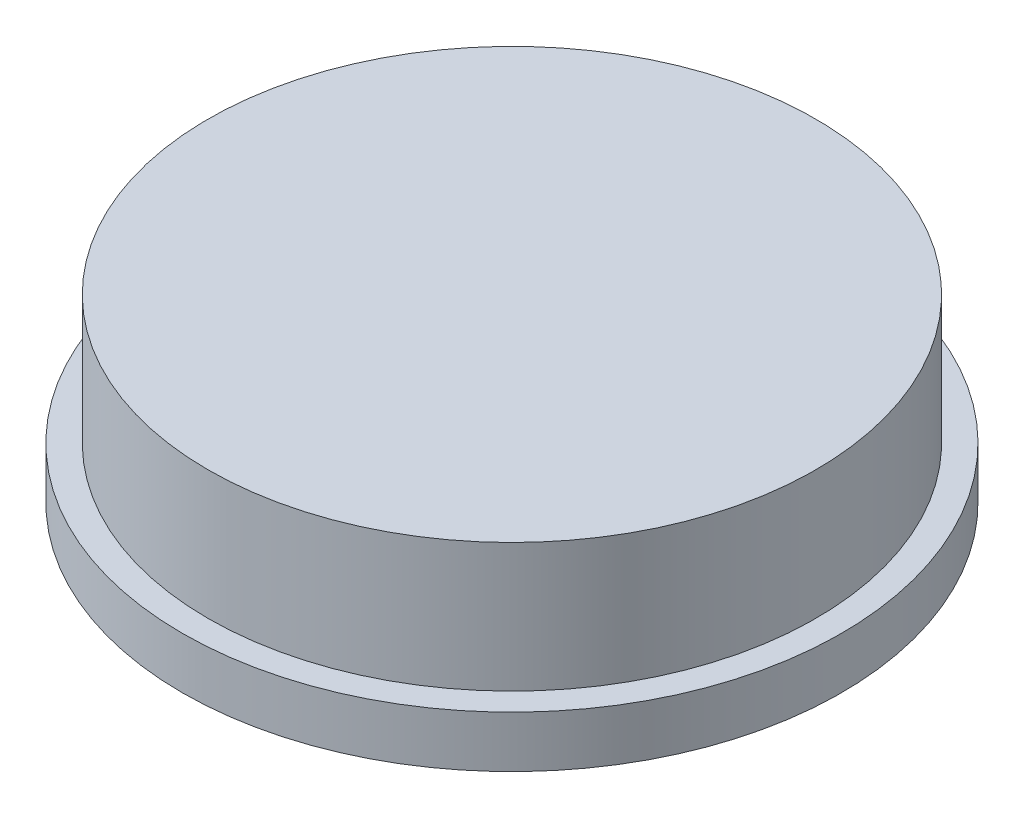
SolidWorks part; units mm, degrees
ref_plane "Front Plane" through (0, 0, 0) normal (0, 0, 1) x (1, 0, 0)
ref_plane "Top Plane" through (0, 0, 0) normal (0, 1, 0) x (1, 0, 0)
ref_plane "Right Plane" through (0, 0, 0) normal (1, 0, 0) x (0, 0, -1)
sketch "Sketch1" plane through (0, 0, 0) normal (0, 1, 0) x (1, 0, 0)
  circle A0 centre (0, 0) radius 32.512
  point P18 (0, 0)
  point P27 (0, 0)
  point P32 (0, 0)
  dimension "D1" = 65.024
extrude "Boss-Extrude1" add sketch "Sketch1" along normal blind 5.08
sketch "Sketch2" plane through (0, 5.08, 0) normal (0, 1, 0) x (1, 0, 0)
  circle A0 centre (0, 0) radius 29.972
  dimension "D1" = 59.944
extrude "Boss-Extrude2" add sketch "Sketch2" along normal blind 12.7
